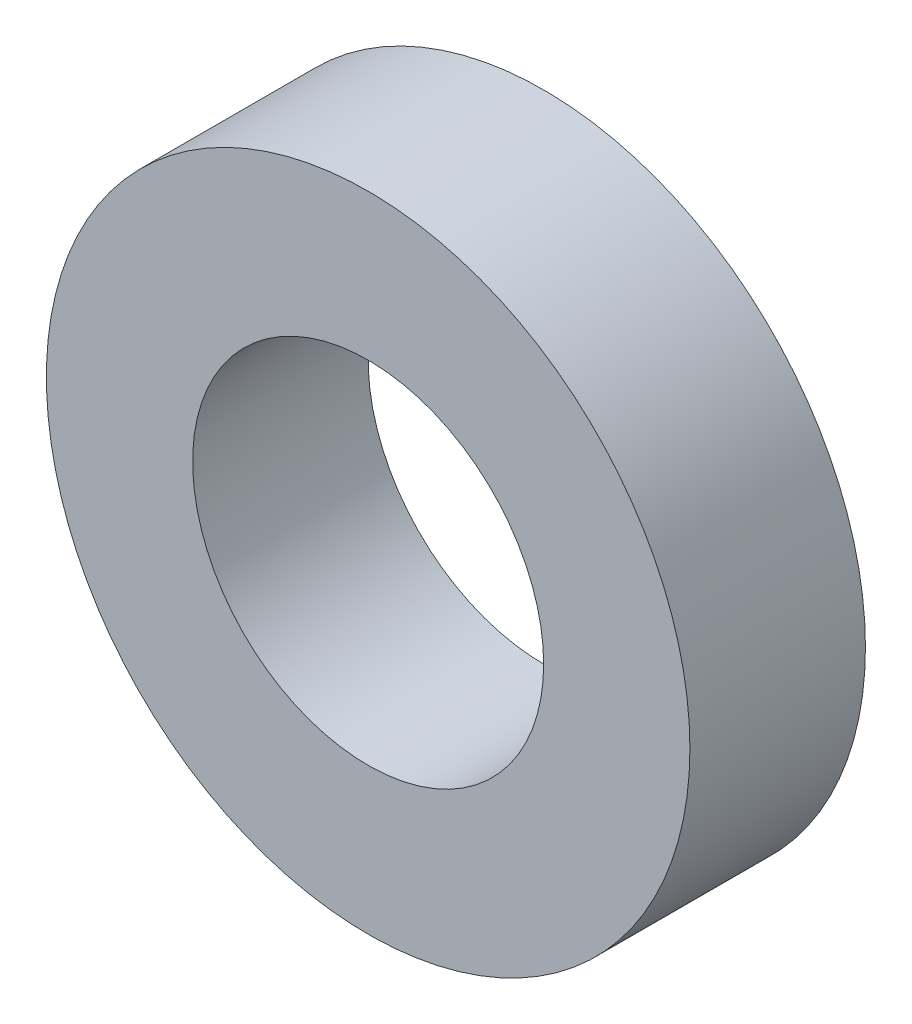
SolidWorks part; units mm, degrees
ref_plane "前视基准面" through (0, 0, 0) normal (0, 0, 1) x (1, 0, 0)
ref_plane "上视基准面" through (0, 0, 0) normal (0, 1, 0) x (1, 0, 0)
ref_plane "右视基准面" through (0, 0, 0) normal (1, 0, 0) x (0, 0, -1)
sketch "草图1" plane through (0, 0, 0) normal (0, 0, 1) x (1, 0, 0)
  circle A0 centre (0, 0) radius 2.75
  circle A1 centre (0, 0) radius 1.5
  dimension "D1" = 5.5
  dimension "D2" = 3
extrude "凸台-拉伸1" add sketch "草图1" along normal blind 1.5
